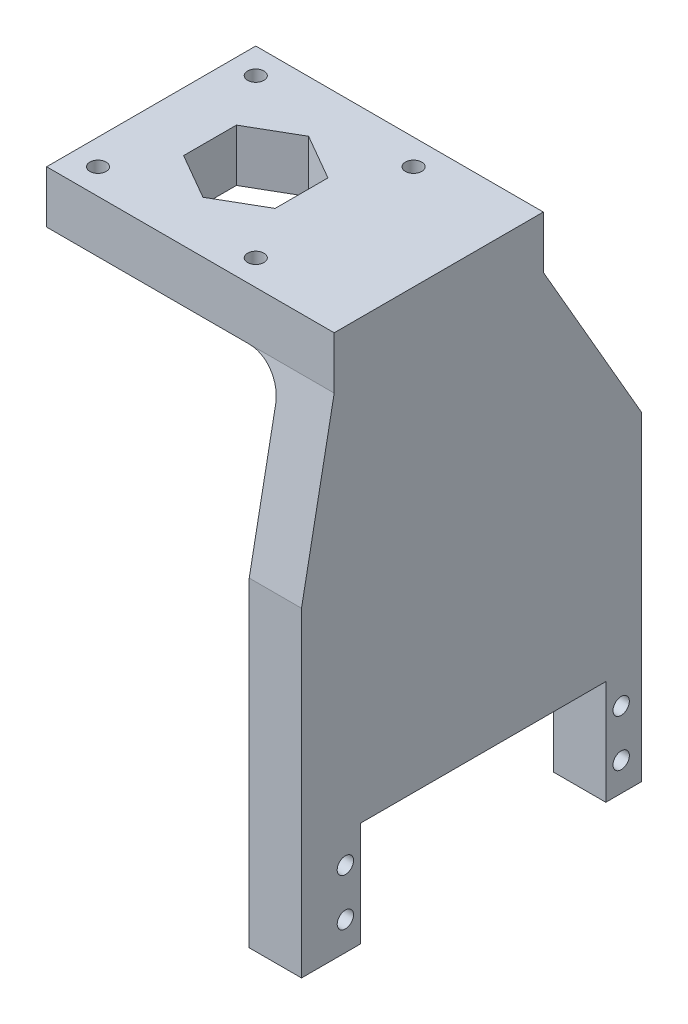
SolidWorks part; units mm, degrees
ref_plane "Front Plane" through (0, 0, 0) normal (0, 0, 1) x (1, 0, 0)
ref_plane "Top Plane" through (0, 0, 0) normal (0, 1, 0) x (1, 0, 0)
ref_plane "Right Plane" through (0, 0, 0) normal (1, 0, 0) x (0, 0, -1)
sketch "Sketch1" plane through (0, 0, 0) normal (0, 0, 1) x (1, 0, 0)
  line L0 (-36, 0) -> (0, 0)
  line L1 (0, 0) -> (0, -75)
  line L2 (0, -75) -> (8, -75)
  line L3 (8, -75) -> (8, 8)
  line L4 (8, 8) -> (-36, 8)
  line L5 (-36, 8) -> (-36, 0)
  dimension "D1" = 8
  dimension "D2" = 8
  dimension "D3" = 36
  dimension "D4" = 75
extrude "Boss-Extrude1" add sketch "Sketch1" along normal mid plane 62
sketch "Sketch2" plane through (0, 8, 0) normal (0, 1, 0) x (1, 0, 0)
  line L0 (-20, 0) -> (0, 0) construction
  line L1 (-13, 4.0415) -> (-20, 8.0829)
  line L2 (-20, 8.0829) -> (-27, 4.0415)
  line L3 (-27, 4.0415) -> (-27, -4.0415)
  line L4 (-27, -4.0415) -> (-20, -8.0829)
  line L5 (-20, -8.0829) -> (-13, -4.0415)
  line L6 (-13, -4.0415) -> (-13, 4.0415)
  circle A0 centre (-20, 0) radius 7 construction
  circle A1 centre (-32.0703, -12.0703) radius 1.25
  circle A2 centre (-32.0703, 12.0703) radius 1.25
  circle A3 centre (-7.9297, 12.0703) radius 1.25
  circle A4 centre (-7.9297, -12.0703) radius 1.25
  point P19 (-20, 0)
  dimension "D1" = 14
  dimension "D3" = 2.5
  dimension "D4" = 34.14
  dimension "D5" = 20
  dimension "D2" = 4
extrude "Cut-Extrude1" cut sketch "Sketch2" against normal up to next
sketch "Sketch3" plane through (0, 0, 0) normal (-1, 0, 0) x (0, 0, 1)
  line L0 (-25.56, -67) -> (0, -67) construction
  line L1 (11.94, -75) -> (-25.56, -75)
  line L2 (11.94, -75) -> (11.94, -59)
  line L3 (11.94, -59) -> (-25.56, -59)
  line L4 (-25.56, -75) -> (-25.56, -59)
  line L6 (31, 8) -> (-31, 8) construction
  line L7 (11.19, -74.55) -> (-24.81, -59.45) construction
  line L8 (11.19, -74.55) -> (-24.81, -74.55) construction
  line L9 (11.19, -74.55) -> (11.19, -59.45) construction
  line L10 (11.19, -59.45) -> (-24.81, -59.45) construction
  line L11 (-24.81, -74.55) -> (-24.81, -59.45) construction
  line L12 (-25.56, -75) -> (11.94, -59) construction
  point P4 (0, -67)
  point P16 (-6.81, -67)
  dimension "D1" = 16
  dimension "D2" = 37.5
  dimension "D3" = 75
  dimension "D4" = 11.19
  dimension "D5" = 15.1
  dimension "D6" = 36
extrude "Cut-Extrude2" cut sketch "Sketch3" against normal up to next
sketch "Sketch4" plane through (0, 0, 0) normal (-1, 0, 0) x (0, 0, 1)
  line L0 (11.94, -67) -> (-6.81, -67) construction
  line L1 (11.94, -75) -> (11.94, -59) construction
  line L2 (-6.81, -67) -> (-6.81, -59) construction
  line L4 (11.94, -59) -> (-25.56, -59) construction
  circle A0 centre (14.29, -70.6) radius 1.25
  circle A1 centre (14.29, -63.4) radius 1.25
  circle A2 centre (-27.91, -63.4) radius 1.25
  circle A3 centre (-27.91, -70.6) radius 1.25
  dimension "D1" = 2.5
  dimension "D2" = 7.2
  dimension "D3" = 42.2
extrude "Cut-Extrude3" cut sketch "Sketch4" against normal up to next
sketch "Sketch6" plane through (0, 0, 0) normal (0, -1, 0) x (1, 0, 0)
  line L0 (0, 31) -> (0, -31) construction
  line L1 (0, -16) -> (-36, -16)
  line L2 (0, -16) -> (0, -31)
  line L3 (0, -31) -> (-36, -31)
  line L4 (-36, -16) -> (-36, -31)
  line L5 (-36, 31) -> (-36, -31) construction
  line L6 (-36, 16) -> (0, 16)
  line L7 (-36, 16) -> (-36, 31)
  line L8 (-36, 31) -> (0, 31)
  line L9 (0, 16) -> (0, 31)
  dimension "D1" = 15
extrude "Cut-Extrude4" cut sketch "Sketch6" against normal up to next
sketch "Sketch7" plane through (0, 0, 0) normal (-1, 0, 0) x (0, 0, 1)
  line L0 (-16, 0) -> (-31, -26)
  line L1 (-31, 8) -> (-31, -75) construction
  line L2 (16, 0) -> (21, -26)
  line L3 (31, -75) -> (11.94, -75) construction
  line L4 (21, -75) -> (31, -75)
  line L5 (31, -75) -> (31, 8)
  line L6 (31, 8) -> (16, 8)
  line L7 (16, 8) -> (16, 0)
  line L8 (-16, 0) -> (-16, 8)
  line L9 (-16, 8) -> (-31, 8)
  line L10 (-31, 8) -> (-31, -26)
  line L11 (21, -26) -> (21, -75)
  dimension "D1" = 34
  dimension "D2" = 5
extrude "Cut-Extrude5" cut sketch "Sketch7" against normal up to next
fillet "Fillet1" radius 5 1 edges at (0, 0, 0)
